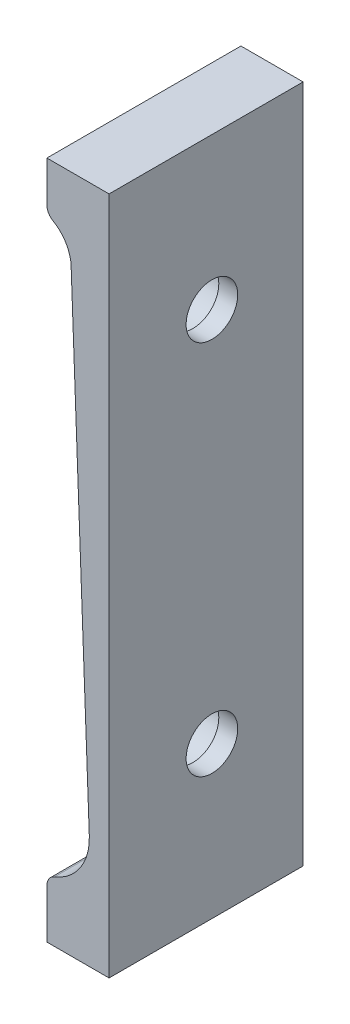
SolidWorks part; units mm, degrees
material "6061-T6 (SS)"
ref_plane "X-Y Datum" through (0, 0, 0) normal (0, 0, 1) x (1, 0, 0)
ref_plane "X-Z Datum" through (0, 0, 0) normal (0, 1, 0) x (1, 0, 0)
ref_plane "Y-Z Datum" through (0, 0, 0) normal (1, 0, 0) x (0, 0, -1)
sketch "Sketch1" plane through (0, 0, 0) normal (0, 0, 1) x (1, 0, 0)
  line L1 (110.6529, 187.6989) -> (94.3715, 187.6989)
  line L7 (94.3715, 9.8989) -> (110.6529, 9.8989)
  line L9 (110.6529, 187.6989) -> (110.6529, 9.8989)
  line L15 (100.7148, 166.3759) -> (102.5116, 118.4949)
  line L16 (102.5116, 118.4949) -> (105.4739, 39.5545)
  line L18 (94.3715, 187.6989) -> (94.3715, 174.9989)
  line L19 (94.3715, 9.8989) -> (94.3715, 25.0884)
  arc A3 (94.3715, 25.0884) -> (105.4739, 39.5545) centre (91.1965, 39.0187) ccw
  arc A4 (94.3715, 174.9989) -> (100.7148, 166.3759) centre (91.1965, 166.0187) cw
  point P30 (102.5116, 118.4949)
  dimension "D4" = 177.8
  dimension "D8" = 9.525
  dimension "D10" = 12.7
  dimension "D6" = 16.2814
  dimension "D15" = 126.8214
extrude "Boss-Extrude1" add sketch "Sketch1" along normal mid plane 12.7
sketch "Sketch3" plane through (0, 0, -6.35) normal (0, 0, -1) x (-1, 0, 0)
  line L1 (-110.6529, 187.6989) -> (-94.3715, 187.6989)
  line L2 (-110.6529, 187.6989) -> (-110.6529, 9.8989)
  line L3 (-110.6529, 9.8989) -> (-94.3715, 9.8989)
  line L4 (-94.3715, 187.6989) -> (-94.3715, 9.8989)
extrude "Boss-Extrude2" add sketch "Sketch3" along normal blind 38.1
sketch "Sketch5" plane through (94.3715, 0, 0) normal (-1, 0, 0) x (0, 0, 1)
  line L0 (-20.574, 148.0107) -> (-20.574, 49.5872) construction
  line L1 (-44.45, 9.8989) -> (-44.45, 187.6989) construction
  circle A0 centre (-20.574, 148.0107) radius 6.7577
  circle A1 centre (-20.574, 49.5872) radius 6.7577
  point P5 (-20.574, 148.0107)
  point P6 (-20.574, 49.5872)
  point P9 (-44.45, 98.7989)
  point P10 (-20.574, 98.7989)
  dimension "D2" = 13.5153
  dimension "D1" = 98.4235
  dimension "D3" = 23.876
extrude "Cut-Extrude1" cut sketch "Sketch5" against normal through all
sketch "Sketch6" plane through (94.3715, 0, 0) normal (-1, 0, 0) x (0, 0, 1)
  circle A0 centre (-20.574, 148.0107) radius 8.7641
  circle A1 centre (-20.574, 49.5872) radius 8.7641
  dimension "D1" = 17.5282
extrude "Cut-Extrude2" cut sketch "Sketch6" against normal offset from surface (11.3284 mm away) 4.953 up to face at (110.6529, 141.253, -20.574)
fillet "Fillet1" radius 3.175 2 edges at (94.3715, 25.0884, 0) (94.3715, 174.9989, 0)
sketch "Sketch7" plane through (94.3715, 0, 0) normal (-1, 0, 0) x (0, 0, 1)
  line L0 (-44.45, 9.8989) -> (-44.45, 187.6989) construction
  line L1 (6.35, 9.8989) -> (-44.45, 9.8989) construction
  circle A0 centre (-23.7998, 104.7679) radius 5.7547
  circle A1 centre (-23.7998, 25.3929) radius 5.7547
  point P4 (0, 0)
  point P7 (0, 0)
  point P8 (-23.7998, 142.4449)
  dimension "D1" = 11.5094
  dimension "D2" = 11.5094
  dimension "D3" = 20.6502
  dimension "D4" = 79.375
  dimension "D5" = 15.494
sketch "Sketch8" plane through (94.3715, 0, 0) normal (-1, 0, 0) x (0, 0, 1)
  circle A0 centre (-23.7998, 104.7679) radius 5.7547
  circle A1 centre (-23.7998, 25.3929) radius 5.7547
